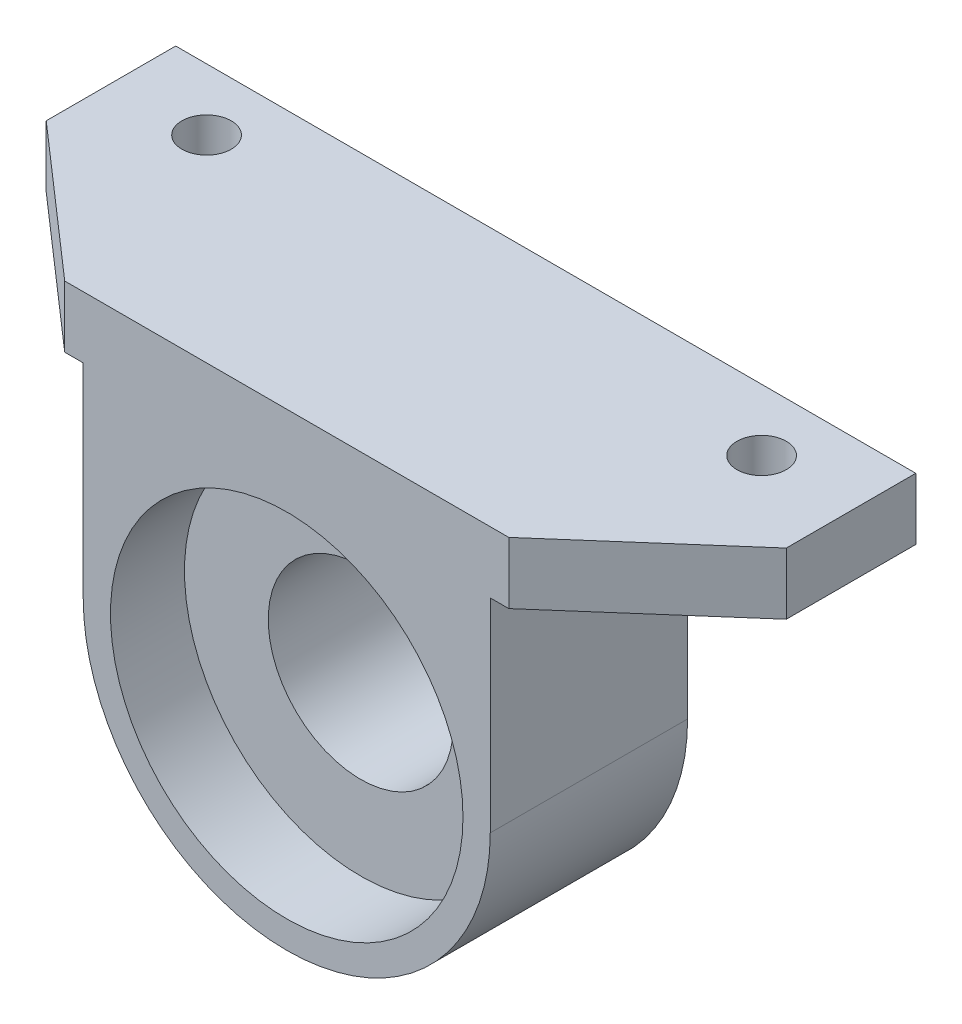
SolidWorks part; units mm, degrees
ref_plane "Plan de face" through (0, 0, 0) normal (0, 0, 1) x (1, 0, 0)
ref_plane "Plan de dessus" through (0, 0, 0) normal (0, 1, 0) x (1, 0, 0)
ref_plane "Plan de droite" through (0, 0, 0) normal (1, 0, 0) x (0, 0, -1)
sketch "Esquisse1" plane through (0, 0, 0) normal (0, 0, 1) x (1, 0, 0)
  circle A0 centre (0, 0) radius 14.29
  circle A1 centre (0, 0) radius 16.5
  dimension "D1" = 28.58
  dimension "D2" = 33
extrude "Boss.-Extru.1" add sketch "Esquisse1" along normal blind 6
sketch "Esquisse2" plane through (0, 0, 0) normal (0, 0, -1) x (-1, 0, 0)
  circle A0 centre (0, 0) radius 16.5
extrude "Boss.-Extru.2" add sketch "Esquisse2" along normal blind 10
ref_plane "Plan2" through (0, 16.5, 0) normal (0, 1, 0) x (1, 0, 0)
sketch "Esquisse3" plane through (0, 16.5, 0) normal (0, 1, 0) x (1, 0, 0)
  line L0 (16.5, 10) -> (-16.5, 10) construction
  line L1 (0, 10) -> (40, 10)
  line L3 (0, -10) -> (40, -10)
  line L4 (40, 10) -> (40, -10)
  line L6 (0, 10) -> (-40, 10)
  line L8 (0, -10) -> (-40, -10)
  line L9 (-40, 10) -> (-40, -10)
  dimension "D1" = 40
  dimension "D2" = 40
  dimension "D3" = 20
extrude "Boss.-Extru.3" add sketch "Esquisse3" along normal blind 5 separate body
ref_plane "Plan3" through (0, 0, -10) normal (0, 0, 1) x (1, 0, 0)
sketch "Esquisse4" plane through (0, 0, -10) normal (0, 0, 1) x (1, 0, 0)
  line L0 (16.5, 16.5) -> (16.5, 0)
  line L1 (8.8, 16.5) -> (-8.8, 16.5) construction
  line L2 (-16.5, 16.5) -> (-16.5, 0)
  line L3 (40, 16.5) -> (-40, 16.5) construction
  line L4 (16.5, 16.5) -> (0, 16.5)
  line L5 (0, 16.5) -> (-16.5, 16.5)
  arc A0 (16.5, 0) -> (0, 16.5) centre (0, 0) ccw
  arc A1 (-16.5, 0) -> (0, 16.5) centre (0, 0) ccw
  circle A2 centre (0, 0) radius 16.5
  dimension "D1" = 16.5
  dimension "D2" = 16.5
  dimension "D3" = 16.5
  dimension "D4" = 16.5
extrude "Boss.-Extru.4" add sketch "Esquisse4" along normal blind 16 contours A2 L5 L2 | A0 L0 L4
sketch "Esquisse7" plane through (0, 21.5, 0) normal (0, 1, 0) x (1, 0, 0)
  line L0 (-40, -10) -> (40, -10) construction
  line L1 (15, -10) -> (-15, -10)
  line L2 (15, -10) -> (15, 10)
  line L3 (15, 10) -> (-15, 10)
  line L4 (-15, -10) -> (-15, 10)
  line L5 (-18.15, 10) -> (18.15, 10) construction
  line L7 (-40, 10) -> (-15, 10)
  line L8 (40, -10) -> (15, -10)
  line L9 (40, -10) -> (40, 10)
  line L10 (40, 10) -> (15, 10)
  line L11 (15, -10) -> (15, 10)
  line L12 (-40, 10) -> (-40, 15)
  line L13 (-40, 15) -> (-15, 15)
  line L14 (-15, 10) -> (-40, 10)
  line L15 (-15, 10) -> (-15, -10)
  line L16 (-15, -10) -> (-40, -10)
  line L17 (-40, 10) -> (-40, -10)
  line L18 (40, -10) -> (30, -10)
  line L19 (40, -10) -> (40, 10)
  line L20 (40, 10) -> (30, 10)
  line L21 (30, -10) -> (30, 10)
  line L22 (-40, -10) -> (-30, -10)
  line L23 (-40, -10) -> (-40, 10)
  line L24 (-40, 10) -> (-30, 10)
  line L25 (-30, -10) -> (-30, 10)
  line L26 (-30, -10) -> (30, -10)
  line L27 (-30, -10) -> (-30, -6)
  line L28 (-30, -6) -> (30, -6)
  line L29 (30, -10) -> (30, -6)
  line L30 (-15, 10) -> (-15, 15)
  line L31 (-30, 10) -> (-15, 10)
  line L32 (-30, 10) -> (-30, 15)
  line L33 (-30, 15) -> (-15, 15)
  line L34 (-15, 10) -> (-15, 15)
  line L35 (15, 10) -> (30, 10)
  line L36 (15, 10) -> (15, 15)
  line L37 (15, 15) -> (30, 15)
  line L38 (30, 10) -> (30, 15)
  circle A0 centre (-22.5, 10) radius 2
  circle A1 centre (22.5, 10) radius 2
  line M10 (40, 10) -> (-40, 10)
  line M11 (-40, 10) -> (-40, -10)
  line M12 (-40, -10) -> (40, -10)
  line M13 (40, -10) -> (40, 10)
  dimension "D1" = 4
  dimension "D2" = 4
  dimension "D3" = 15
  dimension "D4" = 30
  dimension "D5" = 10
  dimension "D6" = 10
  dimension "D7" = 7.5
  dimension "D8" = 7.5
  dimension "D9" = 4
  dimension "D10" = 20
  dimension "D11" = 20
  dimension "D12" = 5
  dimension "D13" = 5
extrude "Enlèv. mat.-Extru.1" cut sketch "Esquisse7" against normal through all contours L25 L14 M12 M11 | L21 L8 M13 M10 | A1 | A0 | L27 L26 L29 L28
sketch "Esquisse8" plane through (0, 0, 0) normal (0, 0, 1) x (1, 0, 0)
  circle A0 centre (0, 0) radius 7.5
extrude "Enlèv. mat.-Extru.2" cut sketch "Esquisse8" against normal through all
sketch "Esquisse10" plane through (0, 0, -10) normal (0, 0, -1) x (-1, 0, 0)
  line L1 (-30, 21.5) -> (30, 21.5)
  line L2 (-30, 21.5) -> (-30, 16.5)
  line L3 (-30, 16.5) -> (30, 16.5)
  line L4 (30, 21.5) -> (30, 16.5)
extrude "Boss.-Extru.5" add sketch "Esquisse10" along normal blind 5
sketch "Esquisse11" plane through (0, 21.5, 0) normal (0, 1, 0) x (1, 0, 0)
  line L0 (-30, 4.5) -> (-18, -6)
  line L1 (-30, -6) -> (-30, 15) construction
  line L2 (-18, -6) -> (18, -6)
  line L3 (-30, -6) -> (30, -6) construction
  line L4 (18, -6) -> (30, 4.5)
  line L5 (30, -6) -> (30, 15) construction
  line L7 (18, -6) -> (30, -6)
  line L8 (18, -6) -> (18, 4.5)
  line L9 (18, 4.5) -> (30, 4.5)
  line L10 (30, -6) -> (30, 4.5)
  line L11 (-18, -6) -> (-30, -6)
  line L12 (-18, -6) -> (-18, 4.5)
  line L13 (-18, 4.5) -> (-30, 4.5)
  line L14 (-30, -6) -> (-30, 4.5)
  circle A0 centre (-22.5, 10) radius 2
  circle A1 centre (22.5, 10) radius 2
  line M3 (20.5, 10) -> (24.5, 10)
  line M5 (-24.5, 10) -> (-20.5, 10)
  line M7 (30, -6) -> (30, 15)
  line M9 (-30, 15) -> (-30, -6)
  line M10 (-30, -6) -> (30, -6)
  dimension "D1" = 12
  dimension "D2" = 12
extrude "Enlèv. mat.-Extru.4" cut sketch "Esquisse11" against normal blind 5 contours L0 M9 M10 | L4 M10 M7 | A1 M3 | A0 M5
